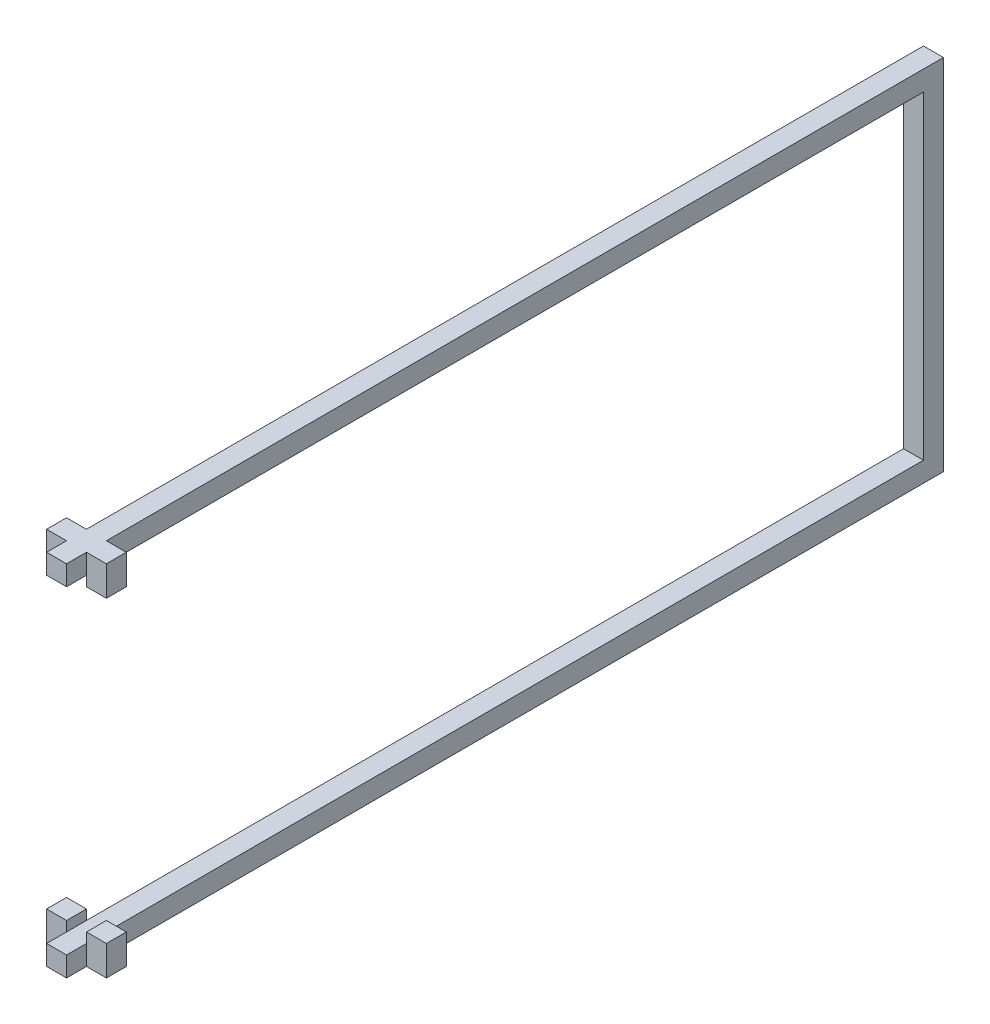
SolidWorks part; units mm, degrees
ref_plane "Front" through (0, 0, 0) normal (0, 0, 1) x (1, 0, 0)
ref_plane "Top" through (0, 0, 0) normal (0, 1, 0) x (1, 0, 0)
ref_plane "Right" through (0, 0, 0) normal (1, 0, 0) x (0, 0, -1)
sketch "Sketch1" plane through (0, 0, 0) normal (0, 0, 1) x (1, 0, 0)
  line L1 (0, 0) -> (-2.54, 0)
  line L2 (0, 0) -> (0, 2.54)
  line L3 (0, 2.54) -> (-2.54, 2.54)
  line L4 (-2.54, 0) -> (-2.54, 2.54)
  dimension "D1" = 2.54
  dimension "D2" = 2.54
extrude "Boss-Extrude1" add sketch "Sketch1" along normal blind 111.76
sketch "Sketch2" plane through (0, 0, 0) normal (0, -1, 0) x (1, 0, 0)
  line L0 (-2.54, 111.76) -> (-2.54, 0) construction
  line L1 (0, 0) -> (-2.54, 0)
  line L2 (0, 0) -> (0, 2.54)
  line L3 (0, 2.54) -> (-2.54, 2.54)
  line L4 (-2.54, 0) -> (-2.54, 2.54)
  dimension "D1" = 2.54
extrude "Boss-Extrude2" add sketch "Sketch2" along normal blind 40.64
sketch "Sketch3" plane through (0, 0, 0) normal (0, 0, -1) x (-1, 0, 0)
  line L1 (2.54, -40.64) -> (0, -40.64)
  line L2 (2.54, -40.64) -> (2.54, -43.18)
  line L3 (2.54, -43.18) -> (0, -43.18)
  line L4 (0, -40.64) -> (0, -43.18)
  dimension "D1" = 2.54
  dimension "D2" = 2.54
extrude "Boss-Extrude3" add sketch "Sketch3" against normal up to surface (111.76 mm away) up to face at (-1.27, 1.27, 111.76)
sketch "Sketch5" plane through (-2.54, 0, 0) normal (-1, 0, 0) x (0, 0, 1)
  line L0 (111.76, 0) -> (2.54, 0) construction
  line L1 (109.22, 2.54) -> (106.68, 2.54)
  line L2 (109.22, 2.54) -> (109.22, 0)
  line L3 (109.22, 0) -> (106.68, 0)
  line L4 (106.68, 2.54) -> (106.68, 0)
  line L5 (111.76, 2.54) -> (0, 2.54) construction
  line L6 (111.76, 2.54) -> (111.76, 0) construction
  dimension "D1" = 2.54
  dimension "D2" = 2.54
extrude "Boss-Extrude4" add sketch "Sketch5" along direction (1, 0, 0) on the side of the normal blind 2.54 contours L2 L1 L4 L3
sketch "Sketch6" plane through (0, 0, 0) normal (1, 0, 0) x (0, 0, -1)
  line L0 (-111.76, 2.54) -> (0, 2.54) construction
  line L1 (-109.22, 0) -> (-106.68, 0)
  line L2 (-109.22, 0) -> (-109.22, 2.54)
  line L3 (-109.22, 2.54) -> (-106.68, 2.54)
  line L4 (-106.68, 0) -> (-106.68, 2.54)
  line L5 (-111.76, 0) -> (-111.76, 2.54) construction
  dimension "D1" = 2.54
  dimension "D2" = 2.54
extrude "Boss-Extrude5" add sketch "Sketch6" along normal blind 2.54
sketch "Sketch7" plane through (0, 0, 0) normal (0, -1, 0) x (-1, 0, 0)
  line L0 (5.08, -106.68) -> (2.54, -106.68) construction
  line L1 (5.08, -109.22) -> (2.54, -109.22)
  line L2 (5.08, -109.22) -> (5.08, -106.68)
  line L3 (5.08, -106.68) -> (2.54, -106.68)
  line L4 (2.54, -109.22) -> (2.54, -106.68)
  line L5 (0, -106.68) -> (-2.54, -106.68)
  line L6 (0, -106.68) -> (0, -109.22)
  line L7 (0, -109.22) -> (-2.54, -109.22)
  line L8 (-2.54, -106.68) -> (-2.54, -109.22)
  line L9 (5.08, -109.22) -> (5.08, -106.68) construction
  line L10 (5.08, -109.22) -> (2.54, -109.22) construction
  line L11 (-2.54, -109.22) -> (-2.54, -106.68) construction
  line L12 (-2.54, -106.68) -> (0, -106.68) construction
  point P10 (0, 0)
  point P11 (0, 0)
  point P14 (0, 0)
extrude "Boss-Extrude6" add sketch "Sketch7" along normal blind 1.27
ref_plane "Plane1" through (0, -20.32, 0) normal (0, -1, 0) x (-1, 0, 0)
mirror "Mirror1" about plane through (0, -20.32, 0) normal (0, -1, 0) of "Boss-Extrude6", "Boss-Extrude4", "Boss-Extrude5"
